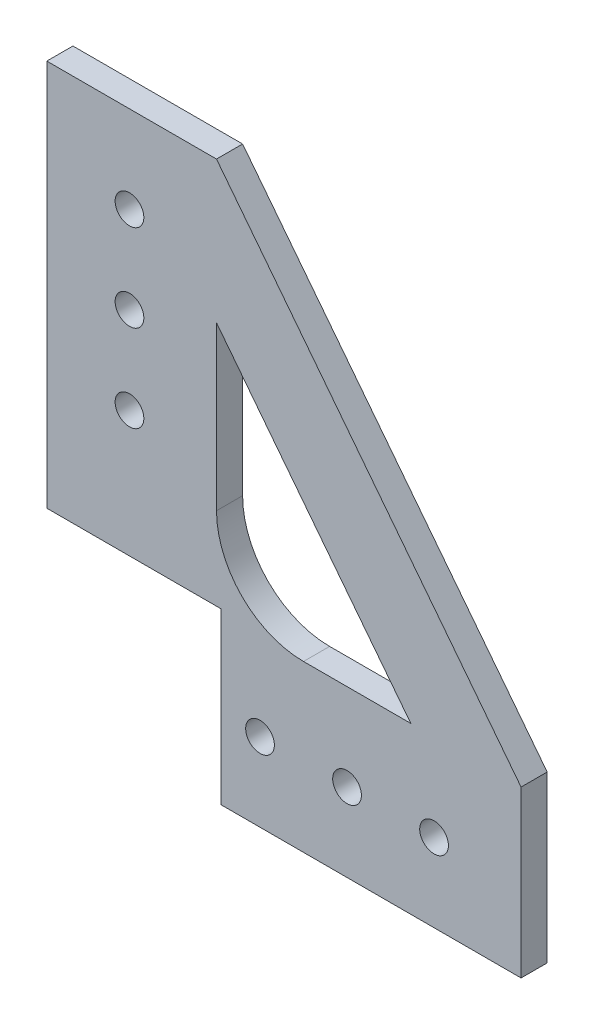
SolidWorks part; units mm, degrees
ref_plane "前视基准面" through (0, 0, 0) normal (0, 0, 1) x (1, 0, 0)
ref_plane "上视基准面" through (0, 0, 0) normal (0, 1, 0) x (1, 0, 0)
ref_plane "右视基准面" through (0, 0, 0) normal (1, 0, 0) x (0, 0, -1)
other "Configuration Table"
sketch "草图1" plane through (0, 0, 0) normal (0, 0, 1) x (1, 0, 0)
  line L0 (10, 0) -> (10, 45) construction
  line L1 (0, 0) -> (20, 0)
  line L2 (0, 0) -> (0, 45)
  line L3 (0, 45) -> (20, 45)
  line L4 (20, 10) -> (20, 28.7118)
  line L5 (30, 0) -> (42.3314, 0)
  line L6 (20, 0) -> (20, -20)
  line L7 (20, -20) -> (55, -20)
  line L8 (55, 0) -> (55, -20)
  line L9 (20, -10) -> (55, -10) construction
  line L10 (20, 45) -> (55, 0)
  line L11 (20, 28.7118) -> (42.3314, 0)
  circle A1 centre (10, 15) radius 1.65
  circle A4 centre (10, 35) radius 1.65
  circle A5 centre (10, 25) radius 1.65
  circle A6 centre (25, -10) radius 1.65
  circle A7 centre (35, -10) radius 1.65
  circle A8 centre (45, -10) radius 1.65
  arc A9 (30, 0) -> (20, 10) centre (30, 10) cw
  dimension "D6" = 10
  dimension "D8" = 3.3
  dimension "D9" = 3.3
  dimension "D10" = 3.3
  dimension "D14" = 3.3
  dimension "D15" = 3.3
  dimension "D16" = 3.3
  dimension "D18" = 10
  dimension "D1" = 20
  dimension "D2" = 20
  dimension "D3" = 45
  dimension "D4" = 35
  dimension "D5" = 15
  dimension "D7" = 10
  dimension "D11" = 5
  dimension "D12" = 10
  dimension "D13" = 10
  dimension "D17" = 10
extrude "凸台-拉伸1" add sketch "草图1" along normal blind 3
sketch "草图2" plane through (0, 0, 3) normal (0, 0, 1) x (1, 0, 0)
  line L0 (20.5, -19) -> (61.4403, -19)
  line L1 (20, 0) -> (20, -20) construction
  line L2 (61.4403, -19) -> (61.4403, -24.7605)
  line L3 (61.4403, -24.7605) -> (16.6017, -23.6707)
  line L5 (20, -20) -> (55, -20) construction
  line L6 (0.5, 0.5) -> (20.5, 0.5)
  line L7 (0, 45) -> (0, 0) construction
  line L8 (20.5, 0.5) -> (20.5, -19)
  line L10 (0, 0) -> (20, 0) construction
  line L11 (0, 0) -> (16.6017, -23.6707)
  line L12 (0.5, 0.5) -> (0.5, 47.4266)
  line L13 (0.5, 47.4266) -> (-5.8509, 46.6681)
  line L14 (-5.8509, 46.6681) -> (0, 0)
  dimension "D1" = 1
  dimension "D2" = 0.5
  dimension "D3" = 0.5
  dimension "D4" = 0.5
extrude "切除-拉伸1" cut sketch "草图2" against normal blind 10
equation "\"3。3\"=11.1759"
